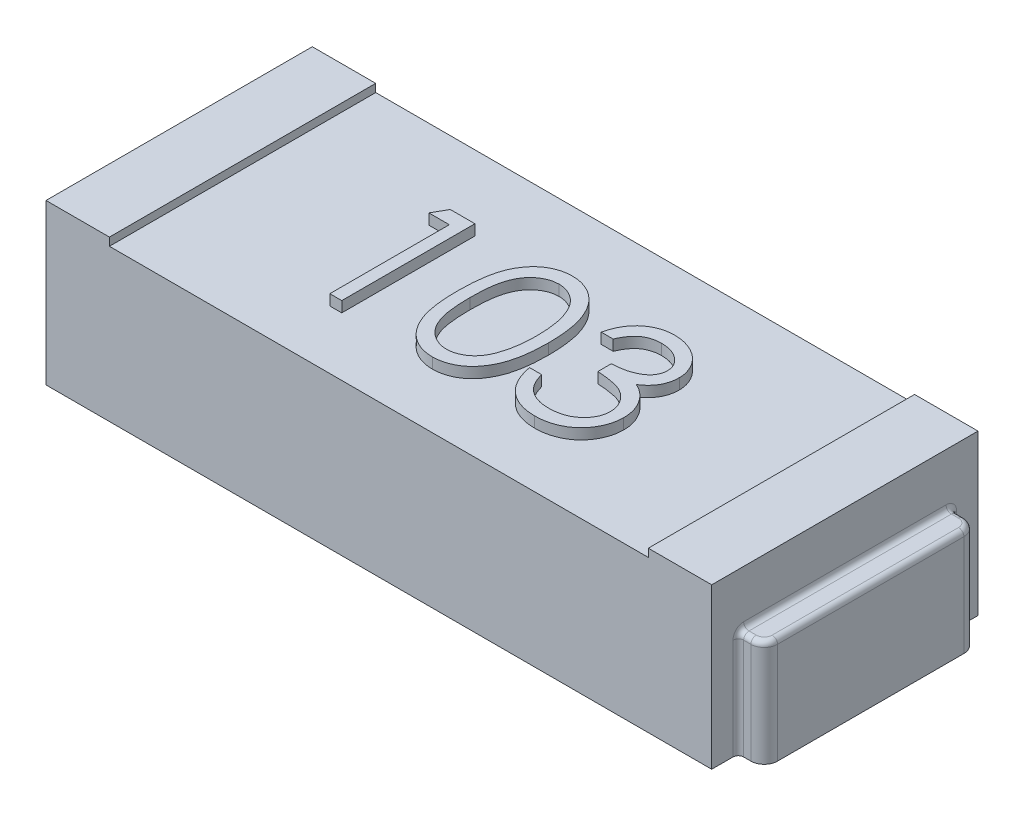
SolidWorks part; units mm, degrees
ref_plane "Plan de face" through (0, 0, 0) normal (0, 0, 1) x (1, 0, 0)
ref_plane "Plan de dessus" through (0, 0, 0) normal (0, 1, 0) x (1, 0, 0)
ref_plane "Plan de droite" through (0, 0, 0) normal (1, 0, 0) x (0, 0, -1)
sketch "Esquisse1" plane through (0, 0, 0) normal (0, 1, 0) x (1, 0, 0)
  line L1 (1.25, -0.5) -> (-1.25, -0.5)
  line L2 (1.25, -0.5) -> (1.25, 0.5)
  line L3 (1.25, 0.5) -> (-1.25, 0.5)
  line L4 (-1.25, -0.5) -> (-1.25, 0.5)
  line L5 (1.25, -0.5) -> (-1.25, 0.5) construction
  line L6 (1.25, 0.5) -> (-1.25, -0.5) construction
  point P0 (0, 0)
  dimension "D1" = 2.5
  dimension "D2" = 1
extrude "Boss.-Extru.1" add sketch "Esquisse1" along normal blind 0.6
sketch "Esquisse2" plane through (0, 0.6, 0) normal (0, 1, 0) x (1, 0, 0)
  line L0 (1.25, 0.5) -> (-1.25, 0.5) construction
  line L1 (1.0118, -0.5) -> (-1.0118, -0.5)
  line L2 (1.0118, -0.5) -> (1.0118, 0.5)
  line L3 (1.0118, 0.5) -> (-1.0118, 0.5)
  line L4 (-1.0118, -0.5) -> (-1.0118, 0.5)
  line L5 (1.0118, -0.5) -> (-1.0118, 0.5) construction
  line L6 (1.0118, 0.5) -> (-1.0118, -0.5) construction
  point P0 (0, 0)
extrude "Enlèv. mat.-Extru.1" cut sketch "Esquisse2" against normal blind 0.03
sketch "Esquisse3" plane through (0, 0, 0) normal (0, 1, 0) x (1, 0, 0)
  line L0 (1.25, -0.5) -> (1.25, 0.5) construction
  line L1 (1.25, 0.4) -> (1.2971, 0.4)
  line L2 (1.25, 0.4) -> (1.25, -0.4)
  line L3 (1.25, -0.4) -> (1.2971, -0.4)
  line L4 (1.3471, 0.35) -> (1.3471, -0.35)
  line L5 (1.25, 0.5) -> (1.0118, 0.5) construction
  line L6 (1.0118, -0.5) -> (1.25, -0.5) construction
  arc A0 (1.2971, -0.4) -> (1.3471, -0.35) centre (1.2971, -0.35) ccw
  arc A1 (1.2971, 0.4) -> (1.3471, 0.35) centre (1.2971, 0.35) cw
  dimension "D1" = 0.05
  dimension "D2" = 0.1
  dimension "D3" = 0.1
extrude "Boss.-Extru.2" add sketch "Esquisse3" along normal blind 0.4
fillet "Congé1" radius 0.02 8 edges at (1.25, 0.2, -0.4) (1.25, 0.2, 0.4) (1.2736, 0.4, -0.4) (1.3325, 0.4, -0.3854) (1.3471, 0.4, 0) (1.3325, 0.4, 0.3854) (1.2736, 0.4, 0.4) (1.25, 0.4, 0)
mirror "Symétrie2" about plane through (0, 0, 0) normal (1, 0, 0) of "Congé1", "Boss.-Extru.2"
sketch "Esquisse4" plane through (0, 0.57, 0) normal (0, 1, 0) x (1, 0, 0)
  line L0 (0.7576, -0.2803) -> (-0.7576, -0.2803) construction
  text T0 "103" font "Century Gothic" height 0.5
  point P0 (0, 0)
  point P3 (0, -0.2803)
extrude "Boss.-Extru.3" add sketch "Esquisse4" along normal blind 0.04
